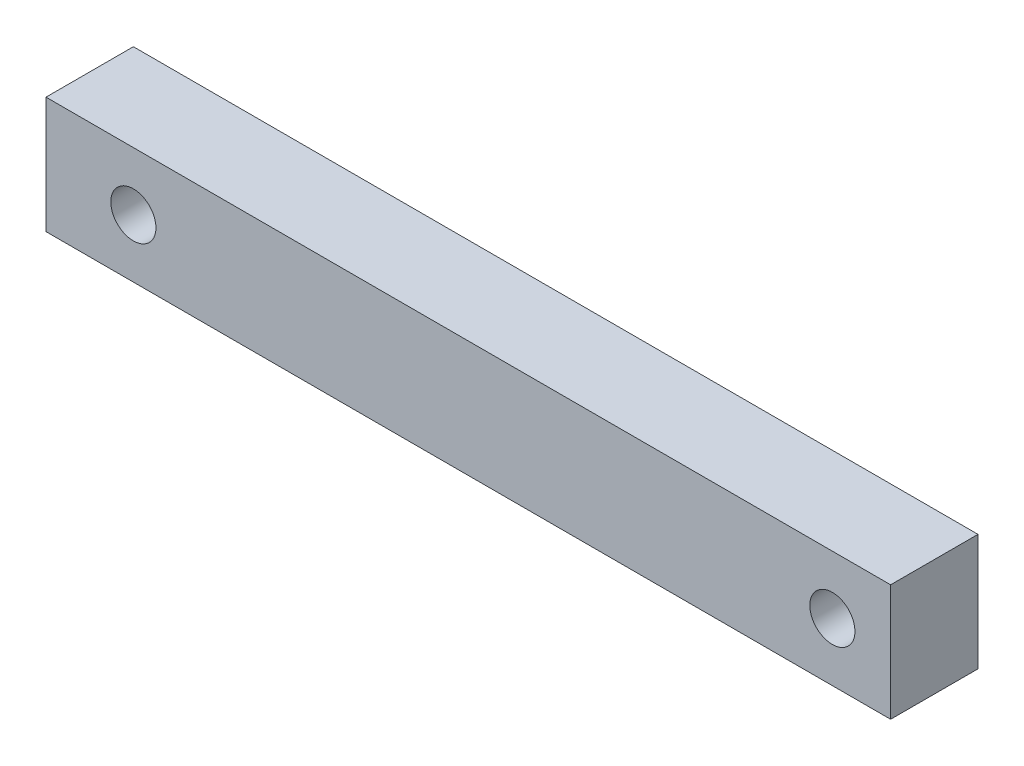
SolidWorks part; units mm, degrees
ref_plane "Płaszczyzna przednia" through (0, 0, 0) normal (0, 0, 1) x (1, 0, 0)
ref_plane "Płaszczyzna górna" through (0, 0, 0) normal (0, 1, 0) x (1, 0, 0)
ref_plane "Płaszczyzna prawa" through (0, 0, 0) normal (1, 0, 0) x (0, 0, -1)
sketch "Szkic1" plane through (0, 0, 0) normal (0, 0, 1) x (1, 0, 0)
  line L1 (35, -366.6195) -> (93, -366.6195)
  line L2 (35, -374.6195) -> (93, -374.6195)
  line L3 (93, -366.6195) -> (93, -374.6195)
  line L4 (35, -366.6195) -> (35, -374.6195)
  line L5 (35, -388.6195) -> (35, -382.6195) construction
  dimension "D1" = 8
  dimension "D2" = 1
  dimension "D3" = 0
extrude "Dodanie-wyciągnięcie1" add sketch "Szkic1" along normal blind 6
sketch "Szkic2" plane through (0, 0, 0) normal (0, 0, -1) x (-1, 0, 0)
  line L0 (-35, -374.6195) -> (-93, -374.6195) construction
  line L1 (-93, -374.6195) -> (-93, -366.6195) construction
  line L3 (-35, -366.6195) -> (-35, -374.6195) construction
  circle A0 centre (-89, -370.6195) radius 1.55
  circle A1 centre (-41, -370.6195) radius 1.55
  dimension "D1" = 3.1
  dimension "D2" = 3.1
  dimension "D3" = 4
  dimension "D4" = 4
  dimension "D5" = 6
  dimension "D6" = 4
extrude "Wytnij-wyciągnięcie1" cut sketch "Szkic2" against normal blind 6
